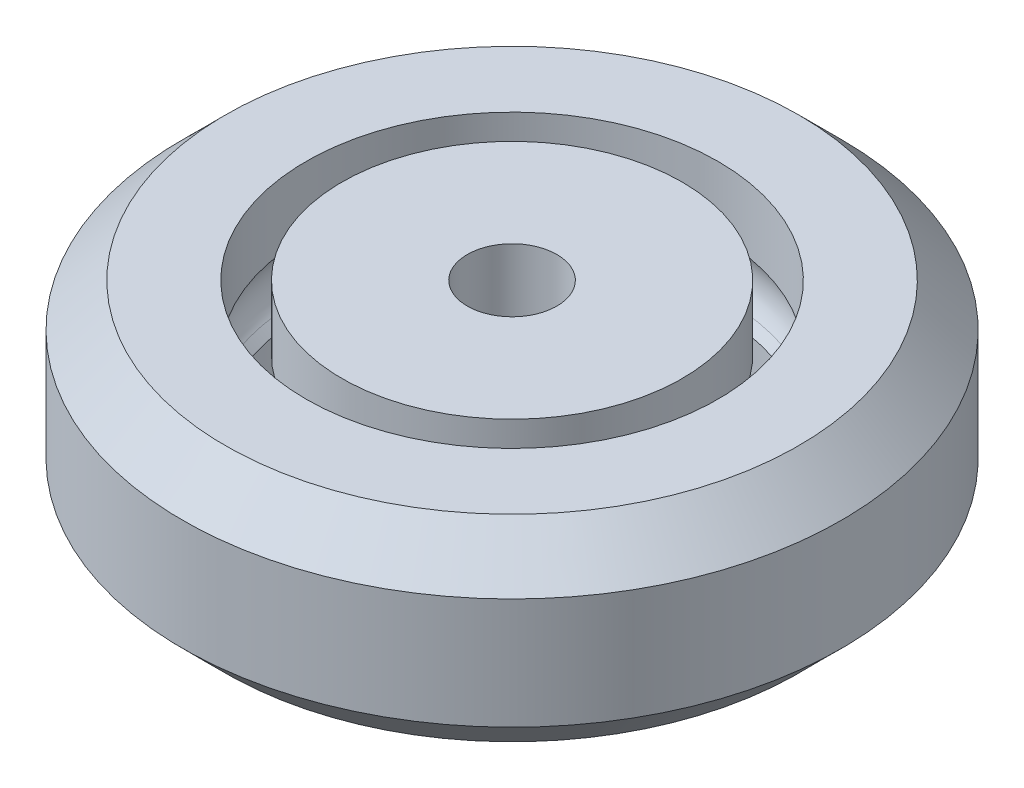
SolidWorks part; units mm, degrees
ref_plane "Front Plane" through (0, 0, 0) normal (0, 0, 1) x (1, 0, 0)
ref_plane "Top Plane" through (0, 0, 0) normal (0, 1, 0) x (1, 0, 0)
ref_plane "Right Plane" through (0, 0, 0) normal (1, 0, 0) x (0, 0, -1)
sketch "Sketch2" plane through (0, 0, 0) normal (0, 0, 1) x (1, 0, 0)
  line L0 (0, 0) -> (0, 19.8196) construction
  line L1 (0, 0) -> (10.5, 0) construction
  line L2 (9.0681, 1.4319) -> (9.5, 1.8638)
  line L3 (10.5, 0) -> (10.5, 10.5941) construction
  line L4 (9.5, 1.8638) -> (9.5, 5.5)
  line L5 (9.5, 5.5) -> (5, 5.5)
  line L6 (5, 5.5) -> (5, -5.5)
  line L7 (11.9319, 1.4319) -> (11.5, 1.8638)
  line L8 (11.5, 1.8638) -> (11.5, 5.5)
  line L9 (11.5, 5.5) -> (16, 5.5)
  line L10 (16, 5.5) -> (16, -5.5)
  line L11 (11.9319, -1.4319) -> (11.5, -1.8638)
  line L12 (9.0681, -1.4319) -> (9.5, -1.8638)
  line L13 (11.5, -5.5) -> (16, -5.5)
  line L14 (11.5, -1.8638) -> (11.5, -5.5)
  line L15 (9.5, -1.8638) -> (9.5, -5.5)
  line L16 (9.5, -5.5) -> (5, -5.5)
  line L17 (16, 0) -> (18.4, 0) construction
  line L18 (18.4, -3.1) -> (18.4, 3.1)
  line L19 (18.4, 3.1) -> (16, 5.5)
  line L20 (18.4, -3.1) -> (16, -5.5)
  line L26 (5, 5.5) -> (2.5, 5.5)
  line L27 (5, 5.5) -> (5, -5.5)
  line L28 (5, -5.5) -> (2.5, -5.5)
  line L29 (2.5, 5.5) -> (2.5, -5.5)
  arc A0 (9.0681, -1.4319) -> (9.0681, 1.4319) centre (10.5, 0) cw
  circle A1 centre (10.5, 0) radius 2 construction
  arc A2 (11.9319, -1.4319) -> (11.9319, 1.4319) centre (10.5, 0) ccw
  point P22 (16, 0)
  point P25 (5, 0)
  point P30 (18.4, 0)
  dimension "D1" = 45
  dimension "D2" = 2.025
  dimension "D3" = 4
  dimension "D4" = 2
  dimension "D5" = 6.2
  dimension "D6" = 45
  dimension "D7" = 11
  dimension "D8" = 5
  dimension "D9" = 10.5
  dimension "D10" = 2.5
  dimension "D11" = 18.4
sketch "Sketch3" plane through (0, 0, 0) normal (0, 0, 1) x (1, 0, 0)
  line L1 (10, -5) -> (11, -5)
  line L2 (10, -5) -> (10, 5)
  line L3 (10, 5) -> (11, 5)
  line L4 (11, -5) -> (11, 5)
  line L5 (10, -5) -> (11, 5) construction
  line L6 (10, 5) -> (11, -5) construction
  line L7 (0, 0) -> (0, 7.9473) construction
  line L8 (0, 0) -> (0, 19.8196) construction
  point P0 (10.5, 0)
  dimension "D1" = 1
  dimension "D2" = 10
sketch "Sketch4" plane through (0, 0, 0) normal (0, 0, 1) x (1, 0, 0)
  line L0 (10, -5) -> (11, 5) construction
  line L3 (10.5, -2.025) -> (10.5, 2.025)
  circle A1 centre (10.5, 0) radius 2.025
  point P4 (10.5, 0)
  point P9 (10.5, 0)
  dimension "D1" = 4.05
revolve "Revolve2" add sketch "Sketch2" angle 360 about L0
